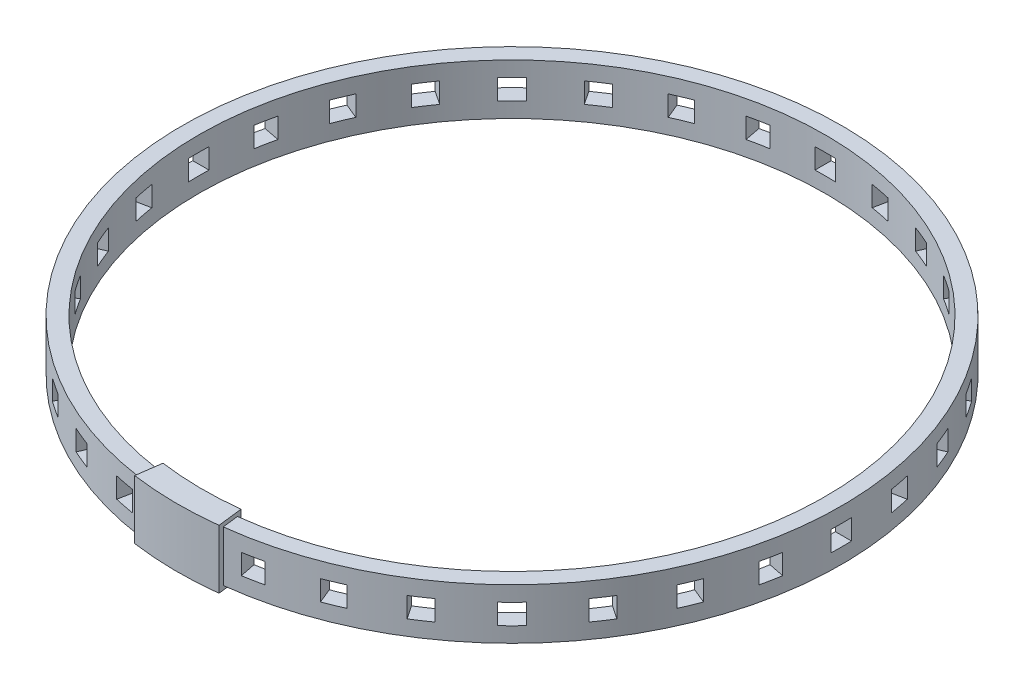
SolidWorks part; units mm, degrees
ref_plane "Front Plane" through (0, 0, 0) normal (0, 0, 1) x (1, 0, 0)
ref_plane "Top Plane" through (0, 0, 0) normal (0, 1, 0) x (1, 0, 0)
ref_plane "Right Plane" through (0, 0, 0) normal (1, 0, 0) x (0, 0, -1)
sketch "Sketch1" plane through (0, 0, 0) normal (0, 1, 0) x (1, 0, 0)
  circle A0 centre (0, 0) radius 81.15
  circle A1 centre (0, 0) radius 77.15
  dimension "D1" = 162.3
  dimension "D2" = 4
extrude "Boss-Extrude1" add sketch "Sketch1" along normal blind 12.5
sketch "Sketch2" plane through (0, 0, 0) normal (0, 0, 1) x (1, 0, 0)
  line L0 (0, 0) -> (0, 6.25) construction
  line L1 (-2.5, 8.75) -> (2.5, 8.75)
  line L2 (-2.5, 8.75) -> (-2.5, 3.75)
  line L3 (-2.5, 3.75) -> (2.5, 3.75)
  line L4 (2.5, 8.75) -> (2.5, 3.75)
  line L5 (-81.15, 0) -> (81.15, 0) construction
  line L6 (-2.5, 8.75) -> (2.5, 3.75) construction
  line L7 (0, 6.25) -> (0, 12.5) construction
  line L8 (77.15, 12.5) -> (-77.15, 12.5) construction
  dimension "D1" = 5
extrude "Cut-Extrude2" cut sketch "Sketch2" against normal through all
pattern_circular "CirPattern1" count 16 every 11.25 about axis through (0, 0, 0) along (0, 1, 0) of "Cut-Extrude2"
sketch "Sketch3" plane through (0, 12.5, 0) normal (0, 1, 0) x (1, 0, 0)
  line L0 (-10.5159, -75.4204) -> (-11.3721, -81.561)
  line L1 (8.9019, -75.6279) -> (9.6267, -81.7854)
  line L2 (8.9019, -75.6279) -> (0, 0) construction
  line L3 (-10.5159, -75.4204) -> (0, 0) construction
  line L4 (0, 0) -> (0, -70.0751) construction
  arc A0 (-10.5159, -75.4204) -> (8.9019, -75.6279) centre (0, 0) ccw
  arc A1 (-11.3721, -81.561) -> (9.6267, -81.7854) centre (0, 0) ccw
  circle A2 centre (0, 0) radius 77.15 construction
  arc A4 (-18.276, -79.0652) -> (-13.3721, -80.0407) centre (0, 0) ccw construction
  arc A5 (-18.276, -79.0652) -> (-13.3721, -80.0407) centre (0, 0) ccw construction
  point P10 (31.0451, -76.274)
  dimension "D1" = 2
  dimension "D2" = 21
  dimension "D4" = 1
  dimension "D3" = 6.2
extrude "Boss-Extrude2" add sketch "Sketch3" along normal blind 1 and the other way offset from surface (13.5 mm away) 1 other way up to face at (0, 0, 81.15)
